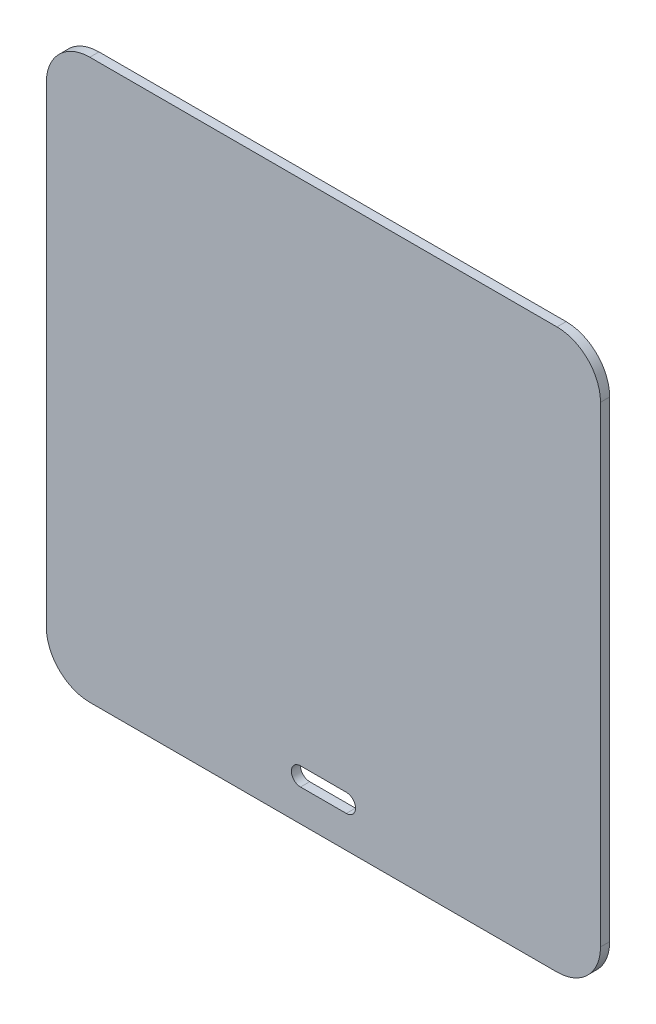
SolidWorks part; units mm, degrees
ref_plane "前视基准面" through (0, 0, 0) normal (0, 0, 1) x (1, 0, 0)
ref_plane "上视基准面" through (0, 0, 0) normal (0, 1, 0) x (1, 0, 0)
ref_plane "右视基准面" through (0, 0, 0) normal (1, 0, 0) x (0, 0, -1)
sketch "草图1" plane through (0, 0, 0) normal (0, 0, 1) x (1, 0, 0)
  line L0 (-49.8462, 0) -> (61.1538, 0) construction
  line L1 (0, 37.0962) -> (0, -41.7115) construction
  line L2 (-30.25, 25.75) -> (-30.25, -25.75)
  line L3 (-25.5, -30.5) -> (25.5, -30.5)
  line L4 (30.25, -25.75) -> (30.25, 25.75)
  line L5 (25.5, 30.5) -> (-25.5, 30.5)
  line L6 (-2.5, -25) -> (2.5, -25)
  line L7 (2.5, -27) -> (-2.5, -27)
  arc A0 (-25.5, 30.5) -> (-30.25, 25.75) centre (-25.5, 25.75) ccw
  arc A1 (25.5, 30.5) -> (30.25, 25.75) centre (25.5, 25.75) cw
  arc A2 (25.5, -30.5) -> (30.25, -25.75) centre (25.5, -25.75) ccw
  arc A3 (-25.5, -30.5) -> (-30.25, -25.75) centre (-25.5, -25.75) cw
  arc A4 (2.5, -27) -> (2.5, -25) centre (2.5, -26) ccw
  arc A5 (-2.5, -27) -> (-2.5, -25) centre (-2.5, -26) cw
  dimension "D3" = 9.5
  dimension "D1" = 2
  dimension "D2" = 2.5
  dimension "D4" = 4.5
  dimension "D5" = 60.5
  dimension "D6" = 61
extrude "凸台-拉伸3" add sketch "草图1" along normal blind 1 contours L7 A5 L6 A4 | L2 A3 L3 A2 L4 A1 L5 A0
